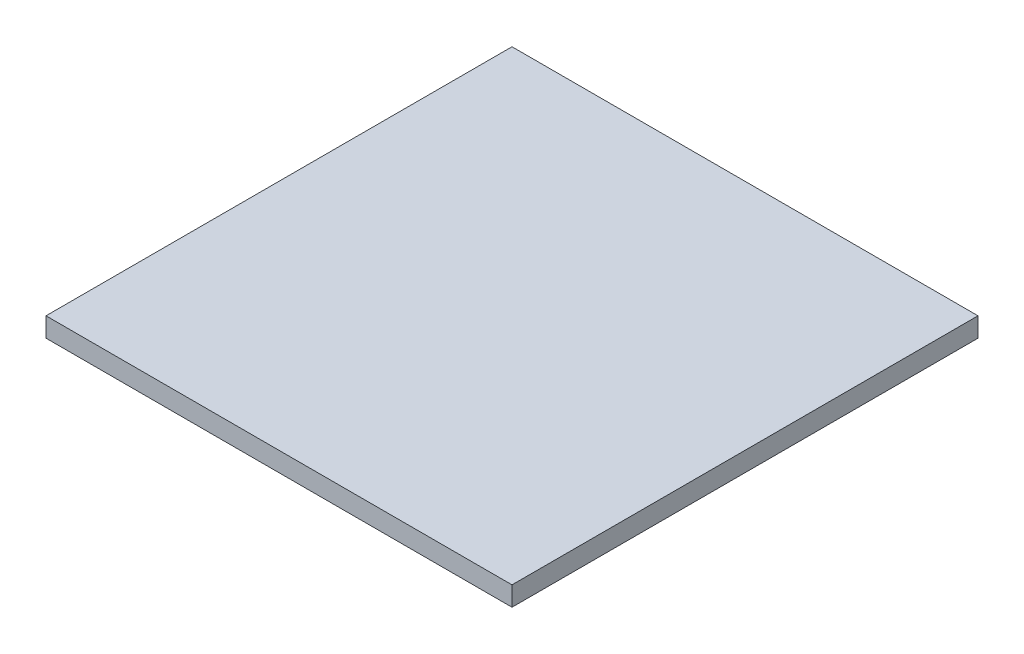
SolidWorks part; units mm, degrees
material "Acrylic (Medium-high impact)"
ref_plane "Front Plane" through (0, 0, 0) normal (0, 0, 1) x (1, 0, 0)
ref_plane "Top Plane" through (0, 0, 0) normal (0, 1, 0) x (1, 0, 0)
ref_plane "Right Plane" through (0, 0, 0) normal (1, 0, 0) x (0, 0, -1)
sketch "Sketch1" plane through (0, 0, 0) normal (0, 1, 0) x (1, 0, 0)
  line L1 (0, 0) -> (76.2, 0)
  line L2 (0, 0) -> (0, 76.2)
  line L3 (0, 76.2) -> (76.2, 76.2)
  line L4 (76.2, 0) -> (76.2, 76.2)
  dimension "D1" = 76.2
  dimension "D2" = 76.2
extrude "Boss-Extrude1" add sketch "Sketch1" along normal blind 3.175
